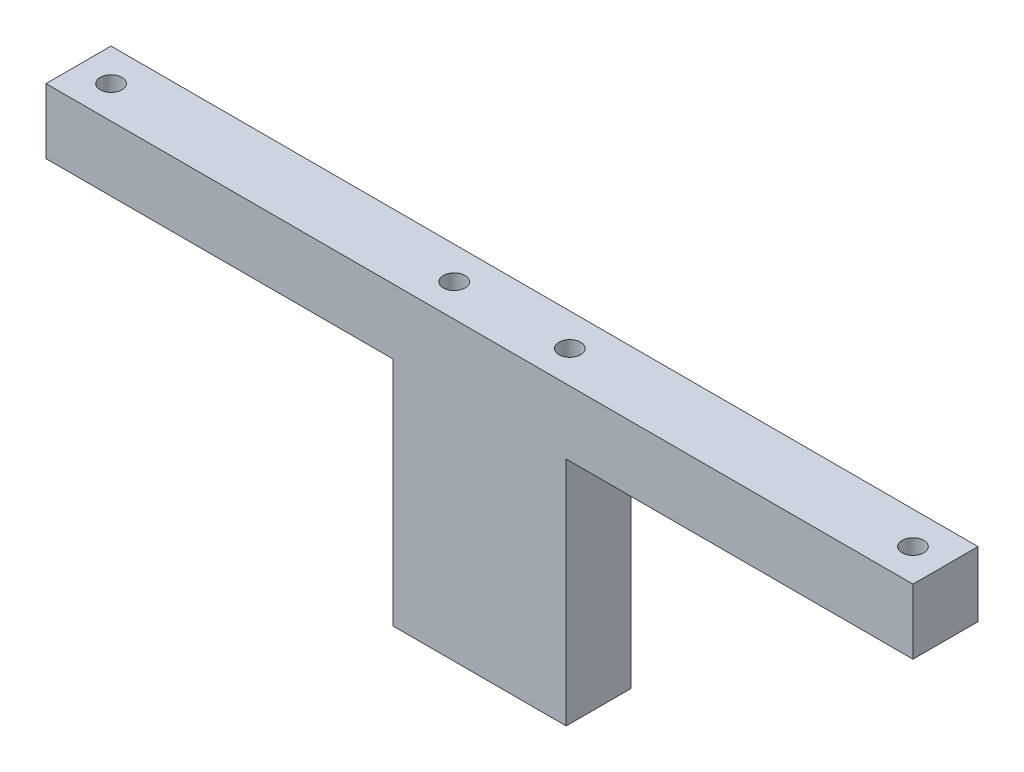
SolidWorks part; units mm, degrees
ref_plane "Front Plane" through (0, 0, 0) normal (0, 0, 1) x (1, 0, 0)
ref_plane "Top Plane" through (0, 0, 0) normal (0, 1, 0) x (1, 0, 0)
ref_plane "Right Plane" through (0, 0, 0) normal (1, 0, 0) x (0, 0, -1)
sketch "Sketch1" plane through (0, 0, 0) normal (0, 0, 1) x (1, 0, 0)
  line L1 (-190.5, 0) -> (190.5, 0)
  line L2 (-190.5, 0) -> (-190.5, -28.575)
  line L3 (-190.5, -28.575) -> (190.5, -28.575)
  line L4 (190.5, 0) -> (190.5, -28.575)
  line L5 (-38.1, -28.575) -> (38.1, -28.575)
  line L6 (-38.1, -28.575) -> (-38.1, -130.175)
  line L7 (-38.1, -130.175) -> (38.1, -130.175)
  line L8 (38.1, -28.575) -> (38.1, -130.175)
  point P8 (0, -28.575)
  point P10 (0, -130.175)
  dimension "D1" = 190.5
  dimension "D2" = 190.5
  dimension "D3" = 381
  dimension "D4" = 28.575
  dimension "D5" = 101.6
  dimension "D6" = 76.2
extrude "Boss-Extrude1" add sketch "Sketch1" along normal blind 28.575 contours L4 L1 L2 L3 | L8 L3 L6 L7
sketch "Sketch2" plane through (0, 0, 0) normal (0, 1, 0) x (1, 0, 0)
  line L0 (0, 0) -> (0, -28.575) construction
  line L1 (-190.5, -28.575) -> (190.5, -28.575) construction
  line L2 (-190.5, -28.575) -> (-190.5, 0) construction
  circle A0 centre (-176.2125, -14.2875) radius 4.7625
  circle A1 centre (-25.4, -14.2875) radius 4.7625
  circle A2 centre (25.4, -14.2875) radius 4.7625
  circle A3 centre (176.2125, -14.2875) radius 4.7625
  point P12 (-190.5, -14.2875)
  point P14 (0, -14.2875)
  dimension "D1" = 9.525
  dimension "D2" = 9.525
  dimension "D3" = 14.2875
  dimension "D4" = 25.4
extrude "Cut-Extrude1" cut sketch "Sketch2" against normal through all
